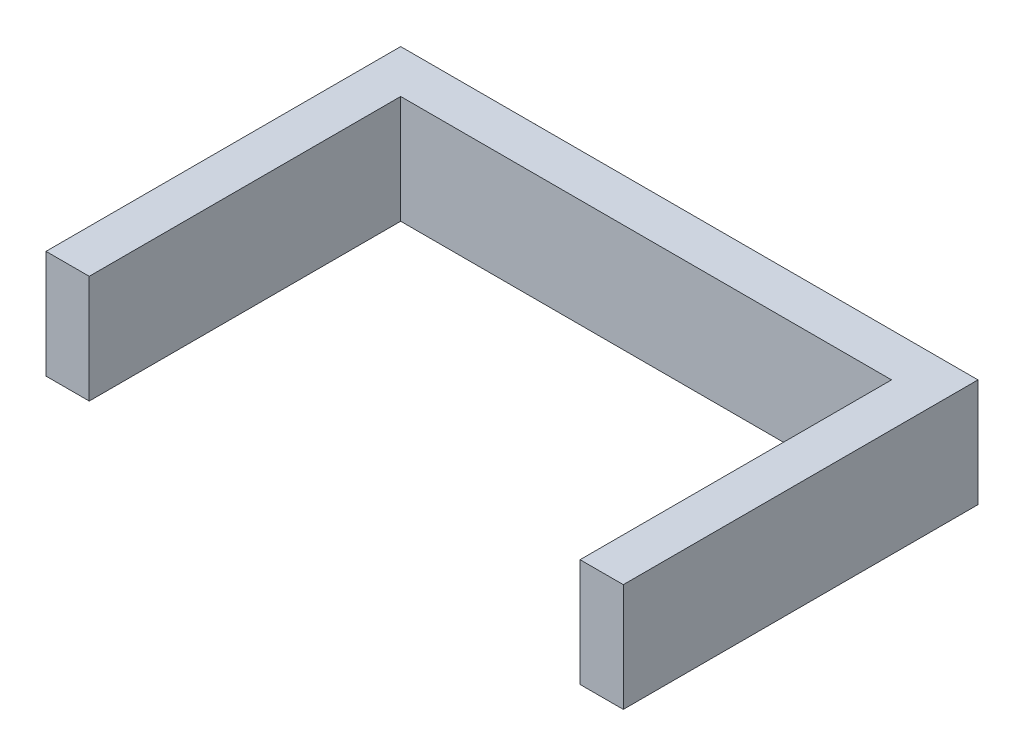
SolidWorks part; units mm, degrees
ref_plane "Front Plane" through (0, 0, 0) normal (0, 0, 1) x (1, 0, 0)
ref_plane "Top Plane" through (0, 0, 0) normal (0, 1, 0) x (1, 0, 0)
ref_plane "Right Plane" through (0, 0, 0) normal (1, 0, 0) x (0, 0, -1)
sketch "Sketch2" plane through (0, 0, 0) normal (0, 1, 0) x (1, 0, 0)
  line L0 (-2, 0) -> (-2, 16.41)
  line L2 (0, 0) -> (0, 14.41)
  line L3 (0, 14.41) -> (22.71, 14.41)
  line L4 (22.71, 0) -> (22.71, 14.41)
  line L5 (-2, 16.41) -> (24.71, 16.41)
  line L6 (24.71, 0) -> (24.71, 16.41)
  line L7 (-2, 0) -> (0, 0)
  line L8 (22.71, 0) -> (24.71, 0)
  dimension "D2" = 22.71
  dimension "D3" = 14.41
  dimension "D1" = 2
extrude "Boss-Extrude1" add sketch "Sketch2" along normal blind 5
